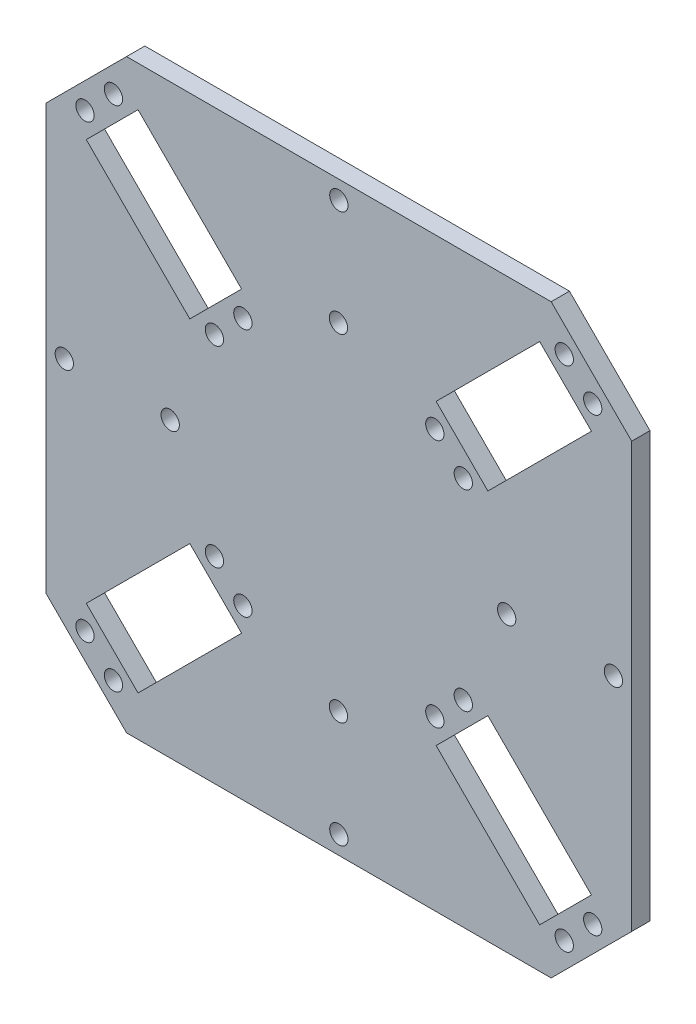
SolidWorks part; units mm, degrees
ref_plane "Plan de face" through (0, 0, 0) normal (0, 0, 1) x (1, 0, 0)
ref_plane "Plan de dessus" through (0, 0, 0) normal (0, 1, 0) x (1, 0, 0)
ref_plane "Plan de droite" through (0, 0, 0) normal (1, 0, 0) x (0, 0, -1)
sketch "Esquisse1" plane through (0, 0, 0) normal (0, 0, 1) x (1, 0, 0)
  line L1 (0, 0) -> (160, 0)
  line L2 (0, 0) -> (0, -160)
  line L3 (0, -160) -> (160, -160)
  line L4 (160, 0) -> (160, -160)
  dimension "D1" = 160
  dimension "D2" = 160
extrude "Boss.-Extru.1" add sketch "Esquisse1" along normal blind 5
chamfer "Chanfrein3" distance 22 angle 45 1 edges at (0, 0, 2.5)
chamfer "Chanfrein4" distance 22 angle 45 3 edges at (0, -160, 2.5) (160, -160, 2.5) (160, 0, 2.5)
sketch "Esquisse3" plane through (0, 0, 5) normal (0, 0, 1) x (1, 0, 0)
  line L0 (25.1431, -10.999) -> (11.001, -25.1412)
  line L1 (25.1431, -10.999) -> (53.4274, -39.2833)
  line L2 (11.001, -25.1412) -> (39.2852, -53.4255)
  line L3 (53.4274, -39.2833) -> (39.2852, -53.4255)
  line L4 (22, 0) -> (0, -22) construction
  dimension "D1" = 20
  dimension "D2" = 40
  dimension "D3" = 5.555
  dimension "D4" = 10
extrude "Enlèv. mat.-Extru.1" cut sketch "Esquisse3" against normal blind 5
ref_plane "Plan2" through (0, -80, 0) normal (0, 1, 0) x (1, 0, 0)
mirror "Symétrie1" about plane through (0, -80, 0) normal (0, 1, 0) of "Enlèv. mat.-Extru.1"
ref_plane "Plan3" through (80, 0, 0) normal (1, 0, 0) x (0, 0, -1)
mirror "Symétrie2" about plane through (80, 0, 0) normal (1, 0, 0) of "Symétrie1", "Enlèv. mat.-Extru.1"
sketch "Esquisse8" plane through (0, 0, 5) normal (0, 0, 1) x (1, 0, 0)
  line L0 (11.001, -25.1412) -> (39.2852, -53.4255) construction
  line L1 (53.4274, -39.2833) -> (25.1431, -10.999) construction
  line L2 (25.1431, -10.999) -> (11.001, -25.1412) construction
  circle A0 centre (10.6474, -18.4237) radius 2.5
  circle A1 centre (18.4256, -10.6455) radius 2.5
  dimension "D3" = 5
  dimension "D4" = 5
  dimension "D1" = 4.5
  dimension "D2" = 4.5
  dimension "D5" = 5
  dimension "D6" = 5
extrude "Enlèv. mat.-Extru.2" cut sketch "Esquisse8" against normal blind 5
mirror "Symétrie3" about plane through (0, -80, 0) normal (0, 1, 0) of "Enlèv. mat.-Extru.2"
mirror "Symétrie4" about plane through (80, 0, 0) normal (1, 0, 0) of "Symétrie3", "Enlèv. mat.-Extru.2"
sketch "Esquisse9" plane through (0, 0, 5) normal (0, 0, 1) x (1, 0, 0)
  line L0 (53.4274, -39.2833) -> (25.1431, -10.999) construction
  line L1 (11.001, -25.1412) -> (39.2852, -53.4255) construction
  line L2 (39.2852, -53.4255) -> (53.4274, -39.2833) construction
  circle A0 centre (53.7809, -46.0008) radius 2.5
  circle A1 centre (46.0027, -53.779) radius 2.5
  dimension "D1" = 5
  dimension "D2" = 5
  dimension "D3" = 4.5
  dimension "D4" = 4.5
  dimension "D5" = 5
  dimension "D6" = 5
extrude "Enlèv. mat.-Extru.3" cut sketch "Esquisse9" against normal blind 5
mirror "Symétrie5" about plane through (0, -80, 0) normal (0, 1, 0) of "Enlèv. mat.-Extru.3"
mirror "Symétrie6" about plane through (80, 0, 0) normal (1, 0, 0) of "Symétrie5", "Enlèv. mat.-Extru.3"
sketch "Esquisse10" plane through (0, 0, 5) normal (0, 0, 1) x (1, 0, 0)
  line L0 (26.8528, -80) -> (79.8858, -26.967)
  line L1 (26.8528, -80) -> (79.8858, -133.033)
  line L2 (79.8858, -26.967) -> (132.9188, -80)
  line L3 (79.8858, -133.033) -> (132.9188, -80)
  line L5 (39.2852, -106.5745) -> (53.4274, -120.7167) construction
  line L7 (39.2852, -53.4255) -> (53.4274, -39.2833) construction
  circle A0 centre (79.8858, -34.0381) radius 2.5
  circle A1 centre (33.9239, -80) radius 2.5
  circle A2 centre (79.8858, -125.9619) radius 2.5
  circle A3 centre (125.8478, -80) radius 2.5
  dimension "D5" = 5
  dimension "D8" = 5
  dimension "D9" = 5
  dimension "D10" = 5
  dimension "D1" = 75
  dimension "D2" = 75
  dimension "D3" = 10
  dimension "D4" = 10
  dimension "D6" = 5
  dimension "D7" = 5
  dimension "D11" = 5
  dimension "D12" = 5
  dimension "D13" = 5
  dimension "D14" = 5
  dimension "D15" = 5
  dimension "D16" = 5
extrude "Enlèv. mat.-Extru.4" cut sketch "Esquisse10" against normal blind 10 contours A3 | A2 | A1 | A0
sketch "Esquisse12" plane through (0, 0, 5) normal (0, 0, 1) x (1, 0, 0)
  line L0 (138, 0) -> (22, 0) construction
  line L1 (0, -22) -> (0, -138) construction
  line L2 (160, -138) -> (160, -22) construction
  line L4 (22, -160) -> (138, -160) construction
  circle A0 centre (5, -80) radius 2.5
  circle A1 centre (155, -80) radius 2.5
  circle A2 centre (80, -155) radius 2.5
  circle A3 centre (80, -5) radius 2.5
  dimension "D3" = 5
  dimension "D5" = 5
  dimension "D7" = 5
  dimension "D10" = 5
  dimension "D1" = 80
  dimension "D2" = 5
  dimension "D4" = 5
  dimension "D6" = 5
  dimension "D8" = 80
  dimension "D9" = 5
extrude "Enlèv. mat.-Extru.5" cut sketch "Esquisse12" against normal blind 10
